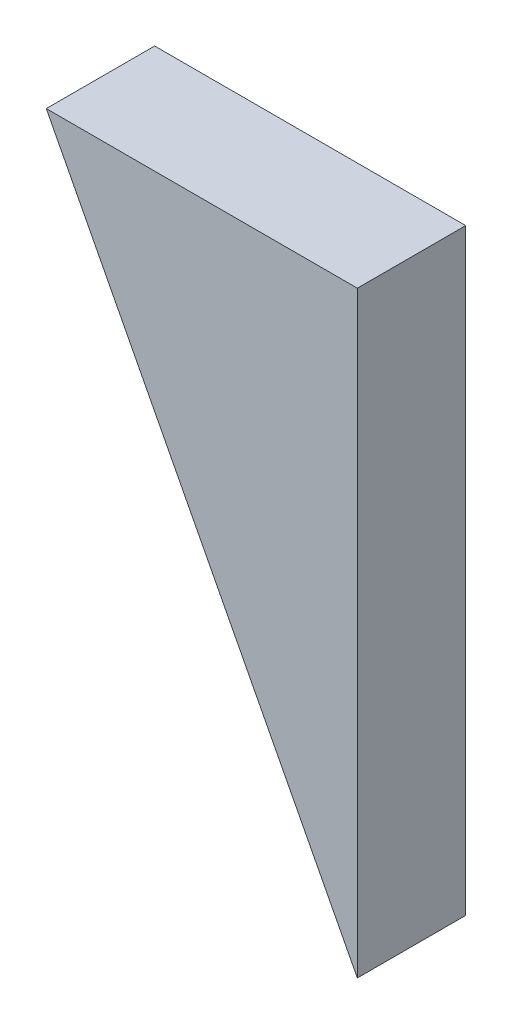
SolidWorks part; units mm, degrees
material "Plain Carbon Steel"
ref_plane "Front Plane" through (0, 0, 0) normal (0, 0, 1) x (1, 0, 0)
ref_plane "Top Plane" through (0, 0, 0) normal (0, 1, 0) x (1, 0, 0)
ref_plane "Right Plane" through (0, 0, 0) normal (1, 0, 0) x (0, 0, -1)
sketch "Sketch1" plane through (0, 0, 0) normal (0, 0, 1) x (1, 0, 0)
  line L0 (0, -15) -> (0, 20)
  line L1 (0, 20) -> (-18.225, 20)
  line L2 (-18.225, 20) -> (0, -15)
  line L3 (-18.225, 37.4997) -> (-18.225, 21.5503) construction
  point P4 (0, 0)
extrude "Boss-Extrude1" add sketch "Sketch1" against normal blind 6.35
